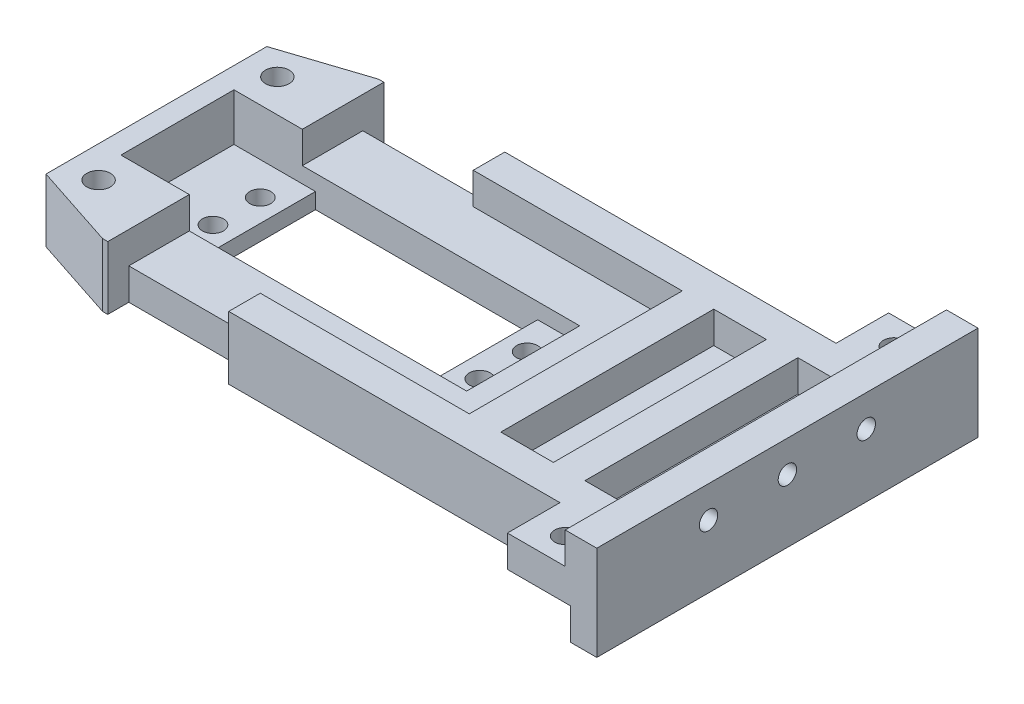
SolidWorks part; units mm, degrees
ref_plane "Front Plane" through (0, 0, 0) normal (0, 0, 1) x (1, 0, 0)
ref_plane "Top Plane" through (0, 0, 0) normal (0, 1, 0) x (1, 0, 0)
ref_plane "Right Plane" through (0, 0, 0) normal (1, 0, 0) x (0, 0, -1)
sketch "Sketch1" plane through (0, 0, 0) normal (0, 1, 0) x (1, 0, 0)
  line L1 (0, 0) -> (120, 0)
  line L2 (0, 0) -> (0, 52.5)
  line L3 (0, 52.5) -> (120, 52.5)
  line L4 (120, 0) -> (120, 52.5)
  dimension "D1" = 120
  dimension "D2" = 52.5
extrude "Boss-Extrude1" add sketch "Sketch1" along normal blind 6
sketch "Sketch2" plane through (0, 6, 0) normal (0, 1, 0) x (1, 0, 0)
  line L0 (0, 0) -> (16, 0)
  line L1 (0, 0) -> (120, 0) construction
  line L2 (16, 0) -> (0, 5.25)
  line L3 (0, 52.5) -> (0, 0) construction
  line L4 (0, 5.25) -> (0, 0)
  line L5 (0, 47.25) -> (0, 52.5)
  line L6 (0, 52.5) -> (16, 52.5)
  line L7 (120, 52.5) -> (0, 52.5) construction
  line L8 (16, 52.5) -> (0, 47.25)
  dimension "D1" = 16
  dimension "D2" = 42
extrude "Cut-Extrude1" cut sketch "Sketch2" against normal up to surface (6 mm away) up to face at (60, 0, -26.25)
sketch "Sketch3" plane through (0, 6, 0) normal (0, 1, 0) x (1, 0, 0)
  line L0 (16, 0) -> (120, 0) construction
  line L1 (17, 0) -> (40, 0)
  line L2 (17, 0) -> (17, 4)
  line L3 (17, 4) -> (40, 4)
  line L4 (40, 0) -> (40, 4)
  line L5 (120, 52.5) -> (16, 52.5) construction
  line L6 (17, 52.5) -> (40, 52.5)
  line L7 (17, 52.5) -> (17, 48.5)
  line L8 (17, 48.5) -> (40, 48.5)
  line L9 (40, 52.5) -> (40, 48.5)
  dimension "D1" = 23
  dimension "D2" = 4
  dimension "D4" = 24
extrude "Cut-Extrude2" cut sketch "Sketch3" against normal up to surface (6 mm away) up to face at (45.3333, 0, -26.25)
sketch "Sketch4" plane through (0, 6, 0) normal (0, 1, 0) x (1, 0, 0)
  line L0 (0, 47.25) -> (0, 5.25) construction
  line L1 (19.5, 37) -> (61.75, 37)
  line L2 (19.5, 37) -> (19.5, 15.5)
  line L3 (19.5, 15.5) -> (61.75, 15.5)
  line L4 (61.75, 37) -> (61.75, 15.5)
  line L5 (17, 48.5) -> (40, 48.5) construction
  dimension "D1" = 19.5
  dimension "D2" = 42.25
  dimension "D3" = 21.5
  dimension "D4" = 11.5
extrude "Cut-Extrude3" cut sketch "Sketch4" against normal up to surface (6 mm away) up to face at (35.7143, 0, -26.25)
sketch "Sketch5" plane through (0, 6, 0) normal (0, 1, 0) x (1, 0, 0)
  line L0 (61.75, 37) -> (19.5, 37) construction
  line L1 (61.75, 15.5) -> (69.75, 15.5)
  line L2 (61.75, 15.5) -> (61.75, 37)
  line L3 (61.75, 37) -> (69.75, 37)
  line L4 (69.75, 15.5) -> (69.75, 37)
  line L5 (19.5, 37) -> (4, 37)
  line L6 (19.5, 37) -> (19.5, 15.5)
  line L7 (19.5, 15.5) -> (4, 15.5)
  line L8 (4, 37) -> (4, 15.5)
  line L9 (0, 47.25) -> (0, 5.25) construction
  line L10 (19.5, 15.5) -> (61.75, 15.5) construction
  dimension "D1" = 8
  dimension "D2" = 4
extrude "Cut-Extrude4" cut sketch "Sketch5" against normal offset from surface (3 mm away) 3 up to face at (40.625, 0, -26.25)
sketch "Sketch6" plane through (0, 6, 0) normal (0, 1, 0) x (1, 0, 0)
  line L0 (120, 0) -> (120, 52.5) construction
  line L1 (120, -10) -> (103, -10)
  line L2 (120, -10) -> (120, 62.5)
  line L3 (120, 62.5) -> (103, 62.5)
  line L4 (103, -10) -> (103, 62.5)
  line L5 (40, 0) -> (120, 0) construction
  line L6 (120, 52.5) -> (40, 52.5) construction
  dimension "D1" = 10
  dimension "D2" = 10
  dimension "D3" = 17
extrude "Boss-Extrude2" add sketch "Sketch6" along normal blind 12
sketch "Sketch7" plane through (0, 6, 0) normal (0, 1, 0) x (1, 0, 0)
  line L0 (103, 26.25) -> (69.75, 26.25)
  line L1 (103, 52.5) -> (103, 0) construction
  line L3 (103, 26.25) -> (103, 0)
  line L4 (103, 0) -> (40, 0)
  line L5 (40, 0) -> (40, 4)
  line L6 (40, 4) -> (17, 4)
  line L7 (17, 4) -> (17, 0)
  line L8 (17, 0) -> (16, 0)
  line L9 (16, 0) -> (0, 5.25)
  line L10 (0, 5.25) -> (0, 26.25)
  line L11 (69.75, 15.5) -> (69.75, 37) construction
  line L12 (69.75, 26.25) -> (69.75, 15.5)
  line L13 (0, 47.25) -> (0, 5.25) construction
  line L14 (0, 26.25) -> (4, 26.25)
  line L16 (4, 37) -> (4, 15.5) construction
  line L17 (4, 26.25) -> (4, 15.5)
  line L18 (4, 15.5) -> (69.75, 15.5)
extrude "Cut-Extrude6" cut sketch "Sketch7" against normal through all
sketch "Sketch8" plane through (0, 18, 0) normal (0, 1, 0) x (1, 0, 0)
  line L0 (103, 62.5) -> (103, -10) construction
  line L1 (103, 26.25) -> (120, 26.25)
  line L2 (103, 26.25) -> (103, -10)
  line L3 (103, -10) -> (120, -10)
  line L4 (120, 26.25) -> (120, -10)
extrude "Cut-Extrude7" cut sketch "Sketch8" against normal through all
sketch "Sketch9" plane through (0, 3, 0) normal (0, 1, 0) x (1, 0, 0)
  line L1 (69.75, 26.25) -> (4, 26.25)
  line L2 (69.75, 26.25) -> (69.75, 15.5)
  line L3 (69.75, 15.5) -> (4, 15.5)
  line L4 (4, 26.25) -> (4, 15.5)
extrude "Cut-Extrude8" cut sketch "Sketch9" against normal blind 6
sketch "Sketch10" plane through (0, 0, -52.5) normal (0, 0, -1) x (-1, 0, 0)
  line L0 (-120, 0) -> (-40, 0) construction
  line L1 (-120, 6) -> (-115, 6)
  line L2 (-120, 6) -> (-120, 0)
  line L3 (-120, 0) -> (-115, 0)
  line L4 (-115, 6) -> (-115, 0)
  dimension "D1" = 5
extrude "Boss-Extrude3" add sketch "Sketch10" along normal up to surface (10 mm away) up to face at (111.5, 12, -62.5)
sketch "Sketch14" plane through (0, 3, 0) normal (0, 1, 0) x (1, 0, 0)
  line L0 (69.75, 26.25) -> (61.75, 26.25) construction
  line L1 (61.75, 37) -> (61.75, 26.25) construction
  line L2 (19.5, 26.25) -> (19.5, 37) construction
  circle A0 centre (66, 30.75) radius 2
  circle A1 centre (15.25, 30.75) radius 2
  dimension "D4" = 4
  dimension "D1" = 4.5
  dimension "D2" = 4.25
  dimension "D3" = 4.25
extrude "Cut-Extrude9" cut sketch "Sketch14" against normal up to surface (3 mm away) up to face at (50.8333, 0, -43.8833)
sketch "Sketch15" plane through (0, 6, 0) normal (0, 1, 0) x (1, 0, 0)
  line L0 (0, 47.25) -> (0, 26.25) construction
  line L1 (4, 26.25) -> (0, 26.25) construction
  circle A0 centre (6, 43.25) radius 2.25
  dimension "D1" = 4.5
  dimension "D2" = 6
  dimension "D3" = 17
extrude "Cut-Extrude10" cut sketch "Sketch15" against normal through all
sketch "Sketch17" plane through (0, 6, 0) normal (0, -1, 0) x (1, 0, 0)
  line L0 (103, -62.5) -> (103, -52.5) construction
  line L1 (115, -62.5) -> (103, -62.5) construction
  circle A0 centre (109, -57.5) radius 2
  dimension "D1" = 4
  dimension "D2" = 6
  dimension "D3" = 5
extrude "Cut-Extrude11" cut sketch "Sketch17" against normal through all
sketch "Sketch18" plane through (0, 18, 0) normal (0, 1, 0) x (1, 0, 0)
  line L0 (103, 62.5) -> (103, 26.25) construction
  line L1 (103, 46.5) -> (114, 46.5)
  line L2 (103, 46.5) -> (103, 26.25)
  line L3 (103, 26.25) -> (114, 26.25)
  line L4 (114, 46.5) -> (114, 26.25)
  line L5 (120, 26.25) -> (103, 26.25) construction
  line L6 (120, 26.25) -> (120, 62.5) construction
  line L7 (103, 52.5) -> (40, 52.5) construction
  dimension "D1" = 6
  dimension "D2" = 6
extrude "Cut-Extrude12" cut sketch "Sketch18" against normal up to surface (12 mm away) up to face at (6, 6, -41)
sketch "Sketch19" plane through (114, 0, 0) normal (-1, 0, 0) x (0, 0, 1)
  line L0 (-26.25, 6) -> (-26.25, 18) construction
  circle A0 centre (-41.25, 12) radius 1.75
  circle A1 centre (-26.25, 12) radius 1.75
  dimension "D1" = 3.5
  dimension "D2" = 15
extrude "Cut-Extrude13" cut sketch "Sketch19" against normal through all
sketch "Sketch20" plane through (0, 18, 0) normal (0, 1, 0) x (1, 0, 0)
  line L1 (114, 46.5) -> (103, 46.5)
  line L2 (114, 46.5) -> (114, 62.5)
  line L3 (114, 62.5) -> (103, 62.5)
  line L4 (103, 46.5) -> (103, 62.5)
extrude "Cut-Extrude14" cut sketch "Sketch20" against normal blind 6
sketch "Sketch21" plane through (0, 6, 0) normal (0, 1, 0) x (1, 0, 0)
  line L1 (103, 46.5) -> (40, 46.5)
  line L2 (103, 46.5) -> (103, 52.5)
  line L3 (103, 52.5) -> (40, 52.5)
  line L4 (40, 46.5) -> (40, 52.5)
extrude "Boss-Extrude6" add sketch "Sketch21" along normal up to surface (6 mm away) up to face at (108.5, 12, -54.5)
mirror "Mirror1" about plane through (103, 0, -26.25) normal (0, 0, -1) of bodies 122 120
sketch "Sketch22" plane through (0, 6, 0) normal (0, 1, 0) x (1, 0, 0)
  line L0 (114, 46.5) -> (40, 46.5) construction
  line L1 (85.75, 46.5) -> (79.75, 46.5)
  line L2 (85.75, 46.5) -> (85.75, 6)
  line L3 (85.75, 6) -> (79.75, 6)
  line L4 (79.75, 46.5) -> (79.75, 6)
  line L5 (114, 6) -> (40, 6) construction
  line L6 (69.75, 15.5) -> (69.75, 37) construction
  line L8 (95.75, 46.5) -> (101.75, 46.5)
  line L9 (95.75, 46.5) -> (95.75, 6)
  line L10 (95.75, 6) -> (101.75, 6)
  line L11 (101.75, 46.5) -> (101.75, 6)
  dimension "D1" = 6
  dimension "D2" = 10
  dimension "D3" = 10
extrude "Boss-Extrude7" add sketch "Sketch22" along normal up to surface (6 mm away)
sketch "Sketch24" plane through (0, 6, 0) normal (0, 1, 0) x (1, 0, 0)
  line L0 (17, 15.5) -> (17, 0)
  line L1 (16, 0) -> (0, 5.25)
  line L2 (0, 5.25) -> (0, 47.25)
  line L3 (0, 47.25) -> (16, 52.5)
  line L4 (16, 52.5) -> (17, 52.5)
  line L5 (17, 52.5) -> (17, 37)
  line L6 (69.75, 37) -> (4, 37) construction
  line L7 (17, 37) -> (4, 37)
  line L8 (4, 37) -> (4, 15.5)
  line L9 (4, 15.5) -> (17, 15.5)
  line L10 (69.75, 15.5) -> (4, 15.5) construction
  line L11 (17, 0) -> (16, 0)
  circle A0 centre (6, 43.25) radius 2.25
  circle A1 centre (6, 9.25) radius 2.25
extrude "Boss-Extrude8" add sketch "Sketch24" along normal up to surface (6 mm away)
